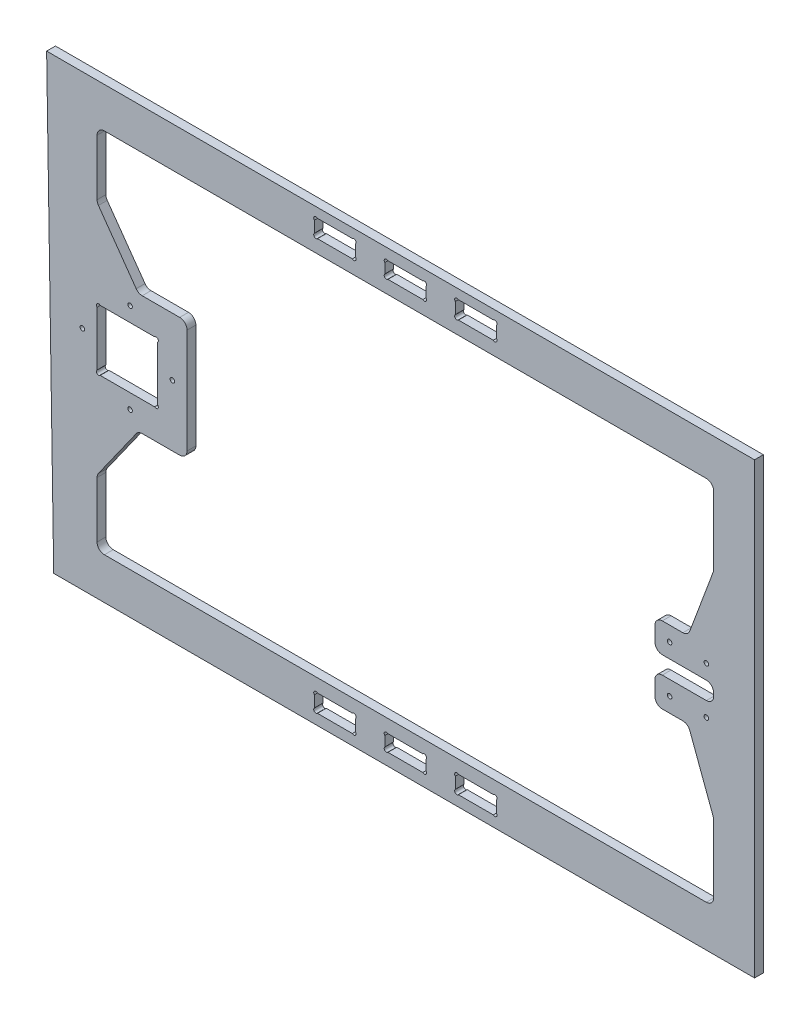
SolidWorks part; units mm, degrees
ref_plane "Alzado" through (0, 0, 0) normal (0, 0, 1) x (1, 0, 0)
ref_plane "Planta" through (0, 0, 0) normal (0, 1, 0) x (1, 0, 0)
ref_plane "Vista lateral" through (0, 0, 0) normal (1, 0, 0) x (0, 0, -1)
sketch "Croquis1" plane through (0, 0, 0) normal (0, 0, 1) x (1, 0, 0)
  line L0 (394.5785, 962.402) -> (468.6932, 962.402)
  line L1 (390.3358, 884.0447) -> (390.3358, 958.1594)
  line L2 (468.6932, 879.802) -> (394.5785, 879.802)
  line L3 (472.9358, 958.1594) -> (472.9358, 884.0447)
  line L4 (742.3358, 1208.8594) -> (742.3358, 1193.3447)
  line L5 (690.5785, 1213.102) -> (738.0932, 1213.102)
  line L6 (686.3358, 1193.3447) -> (686.3358, 1208.8594)
  line L7 (738.0932, 1189.102) -> (690.5785, 1189.102)
  line L8 (934.3358, 648.8594) -> (934.3358, 633.3447)
  line L9 (882.5785, 653.102) -> (930.0932, 653.102)
  line L10 (878.3358, 633.3447) -> (878.3358, 648.8594)
  line L11 (930.0932, 629.102) -> (882.5785, 629.102)
  line L12 (690.5785, 653.102) -> (738.0932, 653.102)
  line L13 (686.3358, 633.3447) -> (686.3358, 648.8594)
  line L14 (738.0932, 629.102) -> (690.5785, 629.102)
  line L15 (742.3358, 648.8594) -> (742.3358, 633.3447)
  line L16 (331.273, 614.5976) -> (321.6325, 1225.9487)
  line L17 (321.6325, 1225.9487) -> (1286.0139, 1225.9487)
  line L18 (1286.0139, 1225.9487) -> (1286.0139, 614.5976)
  line L19 (1220.3358, 671.102) -> (400.3358, 671.102)
  line L20 (1230.3358, 773.3007) -> (1230.3358, 681.102)
  line L21 (1229.7073, 776.7901) -> (1197.76, 862.5914)
  line L22 (1160.3358, 869.102) -> (1188.3885, 869.102)
  line L23 (1150.3358, 899.102) -> (1150.3358, 879.102)
  line L24 (1220.3358, 909.102) -> (1160.3358, 909.102)
  line L25 (1230.3358, 923.102) -> (1230.3358, 919.102)
  line L26 (1160.3358, 933.102) -> (1220.3358, 933.102)
  line L27 (1150.3358, 963.102) -> (1150.3358, 943.102)
  line L28 (1188.3885, 973.102) -> (1160.3358, 973.102)
  line L29 (1197.76, 979.6127) -> (1229.7073, 1065.414)
  line L30 (1230.3358, 1161.102) -> (1230.3358, 1068.9033)
  line L31 (400.3358, 1171.102) -> (1220.3358, 1171.102)
  line L32 (390.3358, 1084.9392) -> (390.3358, 1161.102)
  line L33 (392.1801, 1079.1527) -> (443.6463, 1006.6154)
  line L34 (502.9358, 1002.402) -> (451.802, 1002.402)
  line L35 (512.9358, 849.802) -> (512.9358, 992.402)
  line L36 (451.802, 839.802) -> (502.9358, 839.802)
  line L37 (443.6463, 835.5886) -> (392.1801, 763.0514)
  line L38 (390.3358, 681.102) -> (390.3358, 757.2648)
  line L39 (786.5785, 653.102) -> (834.0932, 653.102)
  line L40 (782.3358, 635.3447) -> (782.3358, 648.8594)
  line L41 (834.0932, 631.102) -> (786.5785, 631.102)
  line L42 (838.3358, 648.8594) -> (838.3358, 635.3447)
  line L43 (934.3358, 1208.8594) -> (934.3358, 1193.3447)
  line L44 (882.5785, 1213.102) -> (930.0932, 1213.102)
  line L45 (878.3358, 1193.3447) -> (878.3358, 1208.8594)
  line L46 (930.0932, 1189.102) -> (882.5785, 1189.102)
  line L47 (838.3358, 1206.8594) -> (838.3358, 1193.3447)
  line L48 (786.5785, 1211.102) -> (834.0932, 1211.102)
  line L49 (782.3358, 1193.3447) -> (782.3358, 1206.8594)
  line L50 (834.0932, 1189.102) -> (786.5785, 1189.102)
  line L51 (1286.0139, 614.5976) -> (331.273, 614.5976)
  line L52 (810.3957, 1294.6698) -> (810.3957, 460.9831) construction
  arc A0 (472.9358, 958.1594) -> (468.6932, 962.402) centre (470.8145, 960.2807) ccw
  arc A1 (394.5785, 962.402) -> (390.3358, 958.1594) centre (392.4571, 960.2807) ccw
  arc A2 (390.3358, 884.0447) -> (394.5785, 879.802) centre (392.4571, 881.9234) ccw
  arc A3 (468.6932, 879.802) -> (472.9358, 884.0447) centre (470.8145, 881.9234) ccw
  arc A4 (738.0932, 1189.102) -> (742.3358, 1193.3447) centre (740.2145, 1191.2234) ccw
  arc A5 (742.3358, 1208.8594) -> (738.0932, 1213.102) centre (740.2145, 1210.9807) ccw
  arc A6 (690.5785, 1213.102) -> (686.3358, 1208.8594) centre (688.4571, 1210.9807) ccw
  arc A7 (686.3358, 1193.3447) -> (690.5785, 1189.102) centre (688.4571, 1191.2234) ccw
  arc A8 (930.0932, 629.102) -> (934.3358, 633.3447) centre (932.2145, 631.2234) ccw
  arc A9 (934.3358, 648.8594) -> (930.0932, 653.102) centre (932.2145, 650.9807) ccw
  arc A10 (882.5785, 653.102) -> (878.3358, 648.8594) centre (880.4571, 650.9807) ccw
  arc A11 (878.3358, 633.3447) -> (882.5785, 629.102) centre (880.4571, 631.2234) ccw
  arc A12 (742.3358, 648.8594) -> (738.0932, 653.102) centre (740.2145, 650.9807) ccw
  arc A13 (690.5785, 653.102) -> (686.3358, 648.8594) centre (688.4571, 650.9807) ccw
  arc A14 (686.3358, 633.3447) -> (690.5785, 629.102) centre (688.4571, 631.2234) ccw
  arc A15 (738.0932, 629.102) -> (742.3358, 633.3447) centre (740.2145, 631.2234) ccw
  arc A16 (390.3358, 681.102) -> (400.3358, 671.102) centre (400.3358, 681.102) ccw
  arc A17 (1220.3358, 671.102) -> (1230.3358, 681.102) centre (1220.3358, 681.102) ccw
  arc A18 (1230.3358, 773.3007) -> (1229.7073, 776.7901) centre (1220.3358, 773.3007) ccw
  arc A19 (1197.76, 862.5914) -> (1188.3885, 869.102) centre (1188.3885, 859.102) ccw
  arc A20 (1150.3358, 879.102) -> (1160.3358, 869.102) centre (1160.3358, 879.102) ccw
  arc A21 (1160.3358, 909.102) -> (1150.3358, 899.102) centre (1160.3358, 899.102) ccw
  arc A22 (1220.3358, 909.102) -> (1230.3358, 919.102) centre (1220.3358, 919.102) ccw
  arc A23 (1230.3358, 923.102) -> (1220.3358, 933.102) centre (1220.3358, 923.102) ccw
  arc A24 (1150.3358, 943.102) -> (1160.3358, 933.102) centre (1160.3358, 943.102) ccw
  arc A25 (1160.3358, 973.102) -> (1150.3358, 963.102) centre (1160.3358, 963.102) ccw
  arc A26 (1188.3885, 973.102) -> (1197.76, 979.6127) centre (1188.3885, 983.102) ccw
  arc A27 (1229.7073, 1065.414) -> (1230.3358, 1068.9033) centre (1220.3358, 1068.9033) ccw
  arc A28 (1230.3358, 1161.102) -> (1220.3358, 1171.102) centre (1220.3358, 1161.102) ccw
  arc A29 (400.3358, 1171.102) -> (390.3358, 1161.102) centre (400.3358, 1161.102) ccw
  arc A30 (390.3358, 1084.9392) -> (392.1801, 1079.1527) centre (400.3358, 1084.9392) ccw
  arc A31 (443.6463, 1006.6154) -> (451.802, 1002.402) centre (451.802, 1012.402) ccw
  arc A32 (512.9358, 992.402) -> (502.9358, 1002.402) centre (502.9358, 992.402) ccw
  arc A33 (502.9358, 839.802) -> (512.9358, 849.802) centre (502.9358, 849.802) ccw
  arc A34 (451.802, 839.802) -> (443.6463, 835.5886) centre (451.802, 829.802) ccw
  arc A35 (392.1801, 763.0514) -> (390.3358, 757.2648) centre (400.3358, 757.2648) ccw
  arc A36 (838.3358, 648.8594) -> (834.0932, 653.102) centre (836.2145, 650.9807) ccw
  arc A37 (786.5785, 653.102) -> (782.3358, 648.8594) centre (784.4571, 650.9807) ccw
  arc A38 (782.3358, 635.3447) -> (786.5785, 631.102) centre (784.4571, 633.2234) ccw
  arc A39 (834.0932, 631.102) -> (838.3358, 635.3447) centre (836.2145, 633.2234) ccw
  arc A40 (930.0932, 1189.102) -> (934.3358, 1193.3447) centre (932.2145, 1191.2234) ccw
  arc A41 (934.3358, 1208.8594) -> (930.0932, 1213.102) centre (932.2145, 1210.9807) ccw
  arc A42 (882.5785, 1213.102) -> (878.3358, 1208.8594) centre (880.4571, 1210.9807) ccw
  arc A43 (878.3358, 1193.3447) -> (882.5785, 1189.102) centre (880.4571, 1191.2234) ccw
  arc A44 (834.0932, 1189.102) -> (838.3358, 1193.3447) centre (836.2145, 1191.2234) ccw
  arc A45 (838.3358, 1206.8594) -> (834.0932, 1211.102) centre (836.2145, 1208.9807) ccw
  arc A46 (786.5785, 1211.102) -> (782.3358, 1206.8594) centre (784.4571, 1208.9807) ccw
  arc A47 (782.3358, 1193.3447) -> (786.5785, 1189.102) centre (784.4571, 1191.2234) ccw
  circle A48 centre (1170.3358, 889.102) radius 3.1
  circle A49 centre (1220.3358, 889.102) radius 3.1
  circle A50 centre (1220.3358, 953.102) radius 3.1
  circle A51 centre (1170.3358, 953.102) radius 3.1
  circle A52 centre (435.2865, 859.802) radius 3.1
  circle A53 centre (370.3358, 923.2766) radius 3.1
  circle A54 centre (435.2865, 982.402) radius 3.1
  circle A55 centre (492.9358, 923.2766) radius 3.1
extrude "Saliente-Extruir1" add sketch "Croquis1" along normal blind 12
